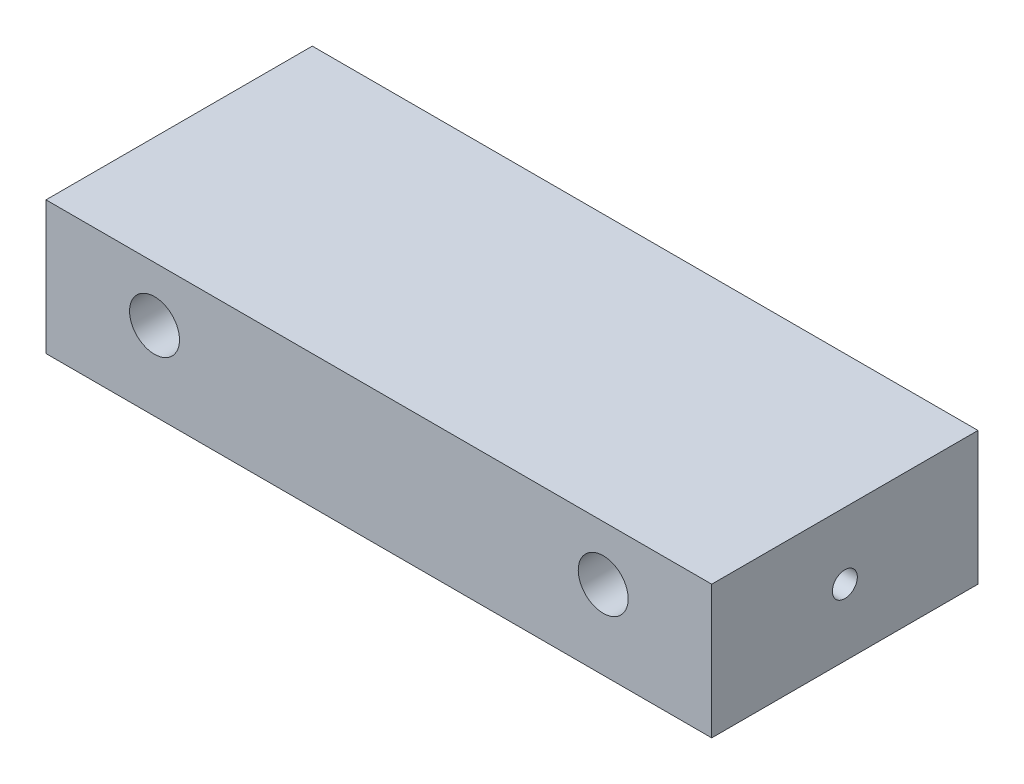
SolidWorks part; units mm, degrees
ref_plane "Front Plane" through (0, 0, 0) normal (0, 0, 1) x (1, 0, 0)
ref_plane "Top Plane" through (0, 0, 0) normal (0, 1, 0) x (1, 0, 0)
ref_plane "Right Plane" through (0, 0, 0) normal (1, 0, 0) x (0, 0, -1)
sketch "Sketch1" plane through (0, 0, 0) normal (0, 0, 1) x (1, 0, 0)
  line L1 (-127, -25.4) -> (127, -25.4)
  line L2 (-127, -25.4) -> (-127, 25.4)
  line L3 (-127, 25.4) -> (127, 25.4)
  line L4 (127, -25.4) -> (127, 25.4)
  line L5 (-127, -25.4) -> (127, 25.4) construction
  line L6 (-127, 25.4) -> (127, -25.4) construction
  point P0 (0, 0)
  dimension "D1" = 254
  dimension "D2" = 50.8
extrude "Boss-Extrude1" add sketch "Sketch1" along normal blind 101.6
sketch "Sketch2" plane through (0, 0, 101.6) normal (0, 0, 1) x (1, 0, 0)
  line L0 (-145.675, 0) -> (145.675, 0) construction
  line L1 (0, -63.2868) -> (0, 63.2868) construction
  line L3 (-127, -25.4) -> (127, -25.4) construction
  circle A0 centre (-85.598, 4.5974) radius 9.525
  circle A1 centre (85.598, 4.5974) radius 9.525
  point P4 (0, 0)
  point P8 (0, 0)
  dimension "D1" = 19.05
  dimension "D2" = 85.598
  dimension "D3" = 29.9974
extrude "Cut-Extrude1" cut sketch "Sketch2" against normal blind 25.4
sketch "Sketch3" plane through (0, 0, 0) normal (0, 0, -1) x (-1, 0, 0)
  line L0 (-177.6914, 0) -> (177.6914, 0) construction
  line L1 (0, -88.4803) -> (0, 88.4803) construction
  circle A0 centre (-57.15, 0) radius 4.7625
  circle A1 centre (57.15, 0) radius 4.7625
  point P4 (0, 0)
  point P8 (0, 0)
  dimension "D1" = 9.525
  dimension "D2" = 57.15
extrude "Cut-Extrude2" cut sketch "Sketch3" against normal blind 25.4
sketch "Sketch4" plane through (127, 0, 0) normal (1, 0, 0) x (0, 0, -1)
  line L0 (-127.6794, 0) -> (127.6794, 0) construction
  line L1 (0, -61.811) -> (0, 61.811) construction
  line L2 (-101.6, -48.701) -> (-101.6, 48.701) construction
  circle A0 centre (-50.8, 0) radius 4.7625
  point P4 (0, 0)
  point P8 (0, 0)
  point P11 (-101.6, 0)
  dimension "D2" = 9.525
  dimension "D1" = 101.6
  dimension "D3" = 50.8
extrude "Cut-Extrude3" cut sketch "Sketch4" against normal blind 25.4
sketch "Sketch5" plane through (-127, 0, 0) normal (-1, 0, 0) x (0, 0, 1)
  line L0 (101.6, 25.4) -> (101.6, -25.4) construction
  circle A0 centre (50.8, 0) radius 4.7625
  dimension "D1" = 9.525
  dimension "D2" = 50.8
extrude "Cut-Extrude4" cut sketch "Sketch5" against normal blind 25.4
thread "Thread1" pitch 1.0583 start angle 0, offset 0, length 25.4, pitch 1.0583, diameter 9.525
ref_plane "Plane1" through (61.9125, 0, 0) normal (0, -1, 0) x (1, 0, 0)
sketch "Thread Profile1" plane through (61.9125, 0, 0) normal (0, -1, 0) x (1, 0, 0)
  line L0 (0, 0) -> (0, 1.0583) construction
  line L1 (0, 0) -> (0.5728, 0.3307)
  line L2 (0.5728, 0.3307) -> (0.5728, 0.463)
  line L3 (0.5728, 0.463) -> (0, 0.7937)
  line L4 (0.5728, 0.3969) -> (0, 0.3969) construction
  line L11 (0, 0) -> (0, 0.7937)
  point P2 (0, 0)
  dimension "Pitch" = 1.0583
  dimension "Profile_Angle" = 60
  dimension "Profile_Land" = 0.1323
  dimension "Profile_Height" = 0.5728
thread "Thread2" pitch 1.0583 start angle 0, offset 0, length 25.4, pitch 1.0583, diameter 9.525
ref_plane "Plane2" through (-52.3875, 0, 0) normal (0, -1, 0) x (1, 0, 0)
sketch "Thread Profile2" plane through (-52.3875, 0, 0) normal (0, -1, 0) x (1, 0, 0)
  line L0 (0, 0) -> (0, 1.0583) construction
  line L1 (0, 0) -> (0.5728, 0.3307)
  line L2 (0.5728, 0.3307) -> (0.5728, 0.463)
  line L3 (0.5728, 0.463) -> (0, 0.7937)
  line L4 (0.5728, 0.3969) -> (0, 0.3969) construction
  line L11 (0, 0) -> (0, 0.7937)
  point P2 (0, 0)
  dimension "Pitch" = 1.0583
  dimension "Profile_Angle" = 60
  dimension "Profile_Land" = 0.1323
  dimension "Profile_Height" = 0.5728
thread "Thread3" pitch 1.0583 start angle 0, offset 0, length 25.4, pitch 1.0583, diameter 9.525
ref_plane "Plane3" through (-127, 0, 46.0375) normal (0, -1, 0) x (0, 0, -1)
sketch "Thread Profile3" plane through (-127, 0, 46.0375) normal (0, -1, 0) x (0, 0, -1)
  line L0 (0, 0) -> (0, 1.0583) construction
  line L1 (0, 0) -> (0.5728, 0.3307)
  line L2 (0.5728, 0.3307) -> (0.5728, 0.463)
  line L3 (0.5728, 0.463) -> (0, 0.7937)
  line L4 (0.5728, 0.3969) -> (0, 0.3969) construction
  line L11 (0, 0) -> (0, 0.7937)
  point P2 (0, 0)
  dimension "Pitch" = 1.0583
  dimension "Profile_Angle" = 60
  dimension "Profile_Land" = 0.1323
  dimension "Profile_Height" = 0.5728
thread "Thread4" pitch 1.0583 start angle 0, offset 0, length 25.4, pitch 1.0583, diameter 9.525
ref_plane "Plane4" through (127, 0, 55.5625) normal (0, -1, 0) x (0, 0, 1)
sketch "Thread Profile4" plane through (127, 0, 55.5625) normal (0, -1, 0) x (0, 0, 1)
  line L0 (0, 0) -> (0, 1.0583) construction
  line L1 (0, 0) -> (0.5728, 0.3307)
  line L2 (0.5728, 0.3307) -> (0.5728, 0.463)
  line L3 (0.5728, 0.463) -> (0, 0.7937)
  line L4 (0.5728, 0.3969) -> (0, 0.3969) construction
  line L11 (0, 0) -> (0, 0.7937)
  point P2 (0, 0)
  dimension "Pitch" = 1.0583
  dimension "Profile_Angle" = 60
  dimension "Profile_Land" = 0.1323
  dimension "Profile_Height" = 0.5728
thread "Thread5" pitch 2.54 start angle 0, offset 0, length 25.4, pitch 2.54, diameter 19.05
ref_plane "Plane5" through (-76.073, 4.5974, 76.2) normal (0, -1, 0) x (1, 0, 0)
sketch "Thread Profile5" plane through (-76.073, 4.5974, 76.2) normal (0, -1, 0) x (1, 0, 0)
  line L0 (0, 0) -> (0, 2.54) construction
  line L1 (0, 0) -> (1.3748, 0.7937)
  line L2 (1.3748, 0.7937) -> (1.3748, 1.1112)
  line L3 (1.3748, 1.1112) -> (0, 1.905)
  line L4 (1.3748, 0.9525) -> (0, 0.9525) construction
  line L11 (0, 0) -> (0, 1.905)
  point P2 (0, 0)
  dimension "Pitch" = 2.54
  dimension "Profile_Angle" = 60
  dimension "Profile_Land" = 0.3175
  dimension "Profile_Height" = 1.3748
thread "Thread6" pitch 2.54 start angle 0, offset 0, length 25.4, pitch 2.54, diameter 19.05
ref_plane "Plane6" through (95.123, 4.5974, 76.2) normal (0, -1, 0) x (1, 0, 0)
sketch "Thread Profile6" plane through (95.123, 4.5974, 76.2) normal (0, -1, 0) x (1, 0, 0)
  line L0 (0, 0) -> (0, 2.54) construction
  line L1 (0, 0) -> (1.3748, 0.7937)
  line L2 (1.3748, 0.7937) -> (1.3748, 1.1112)
  line L3 (1.3748, 1.1112) -> (0, 1.905)
  line L4 (1.3748, 0.9525) -> (0, 0.9525) construction
  line L11 (0, 0) -> (0, 1.905)
  point P2 (0, 0)
  dimension "Pitch" = 2.54
  dimension "Profile_Angle" = 60
  dimension "Profile_Land" = 0.3175
  dimension "Profile_Height" = 1.3748
